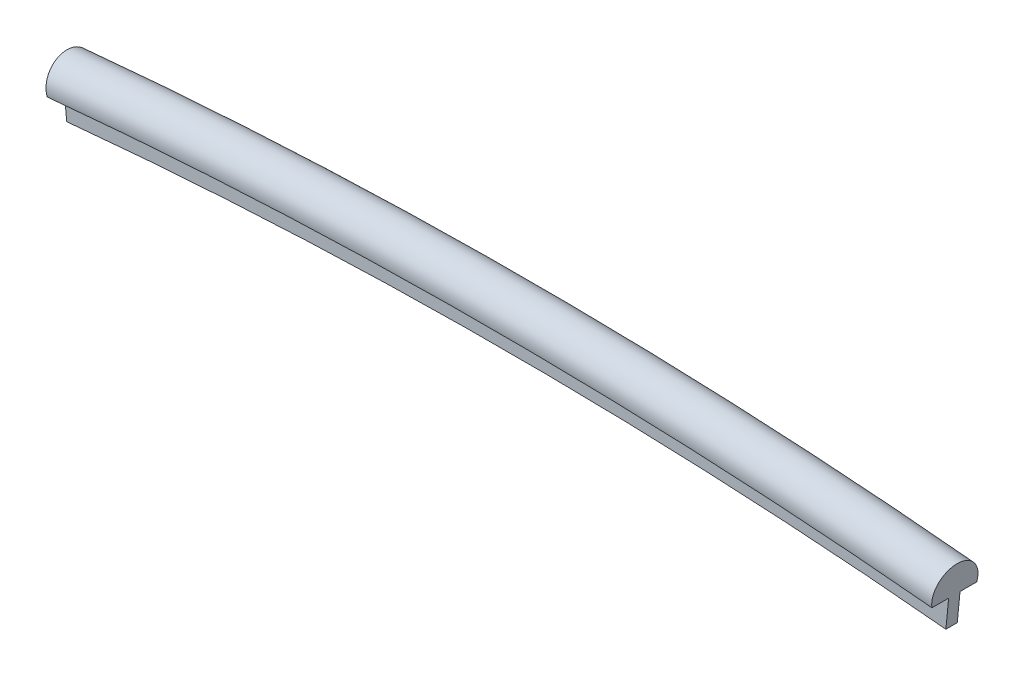
SolidWorks part; units mm, degrees
ref_plane "Front Plane" through (0, 0, 0) normal (0, 0, 1) x (1, 0, 0)
ref_plane "Top Plane" through (0, 0, 0) normal (0, 1, 0) x (1, 0, 0)
ref_plane "Right Plane" through (0, 0, 0) normal (1, 0, 0) x (0, 0, -1)
sketch "Sketch2" plane through (0, 0, 0) normal (1, 0, 0) x (0, 0, -1)
  line L0 (0, 241.3) -> (0, 0) construction
  line L2 (0, 241.3) -> (0, 239.8) construction
  line L3 (0, 239.8) -> (0.3, 239.8)
  line L4 (0, 239.8) -> (-0.3, 239.8)
  line L5 (-0.3, 239.8) -> (-0.3, 241.3)
  line L6 (0.3, 239.8) -> (0.3, 241.3)
  line L7 (0, 241.3) -> (0, 242.8) construction
  line L8 (-1.18, 241.3) -> (-0.3, 241.3)
  line L9 (0.3, 241.3) -> (1.18, 241.3)
  arc A0 (-1.18, 241.3) -> (1.18, 241.3) centre (0, 241.586) cw
  point P14 (0, 241.3)
ref_axis "Axis2" through (0, 0, 70.5976) along (0, 0, -1)
revolve "Revolve1" add sketch "Sketch2" angle 5.54 about axis through (0, 0, 70.5976) along (0, 0, -1)
